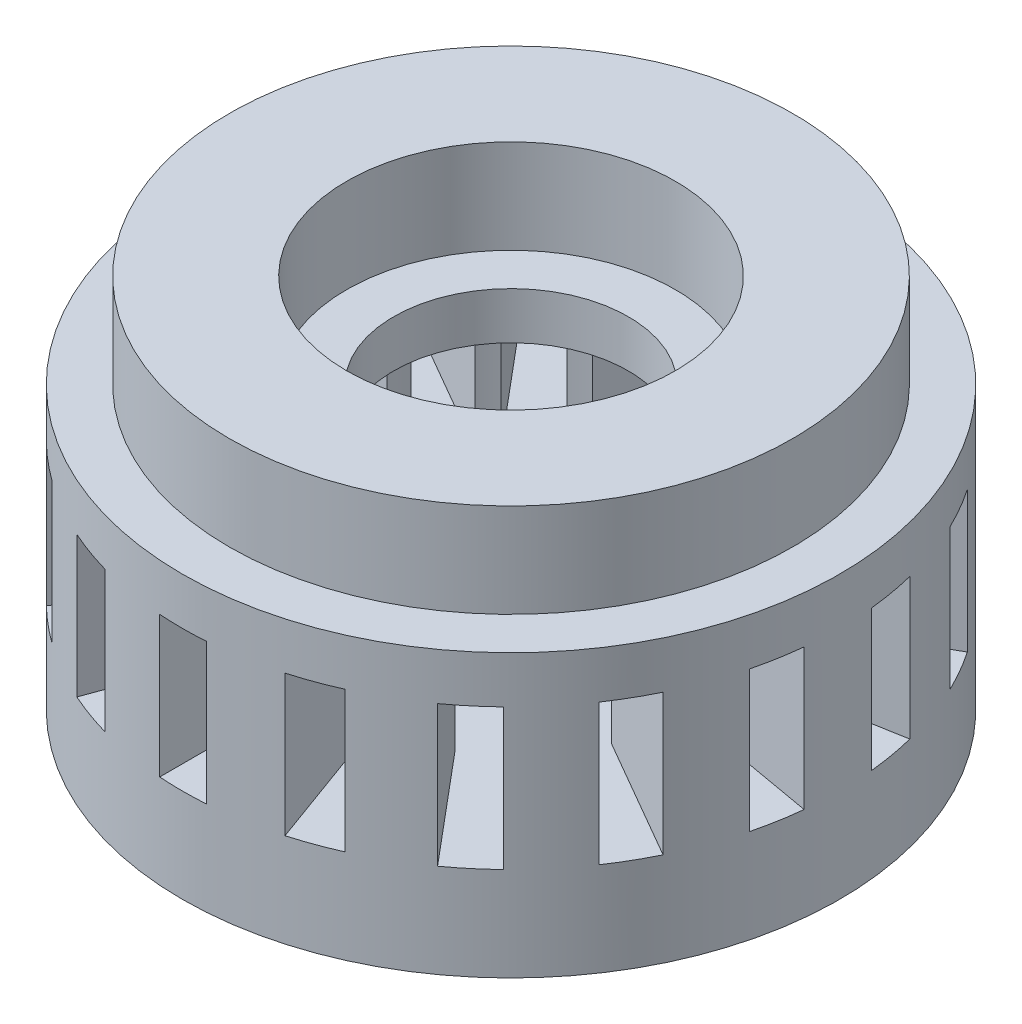
SolidWorks part; units mm, degrees
ref_plane "前视基准面" through (0, 0, 0) normal (0, 0, 1) x (1, 0, 0)
ref_plane "上视基准面" through (0, 0, 0) normal (0, 1, 0) x (1, 0, 0)
ref_plane "右视基准面" through (0, 0, 0) normal (1, 0, 0) x (0, 0, -1)
sketch "草图1" plane through (0, 0, 0) normal (0, 1, 0) x (1, 0, 0)
  line L0 (-1.299, 0.75) -> (1.299, 0.75)
  line L1 (-1.299, 0.75) -> (0, 0) construction
  line L2 (0, 0) -> (1.299, 0.75) construction
  arc A0 (-1.299, 0.75) -> (1.299, 0.75) centre (0, 0) ccw
  circle A1 centre (0, 0) radius 3
  dimension "D1" = 1.5
  dimension "D2" = 6
  dimension "D3" = 120
extrude "凸台-拉伸1" add sketch "草图1" along normal blind 1.5
sketch "草图2" plane through (0, 1.5, 0) normal (0, 1, 0) x (1, 0, 0)
  line L1 (1.299, 0.75) -> (-1.299, 0.75)
  line L2 (1.299, 0.75) -> (-1.299, 0.75)
  circle A0 centre (0, 0) radius 7
  arc A1 (-1.299, 0.75) -> (1.299, 0.75) centre (0, 0) ccw
  arc A2 (-1.299, 0.75) -> (1.299, 0.75) centre (0, 0) ccw
  dimension "D2" = 14
  dimension "D1" = 0
extrude "凸台-拉伸2" add sketch "草图2" along normal blind 2
sketch "草图3" plane through (0, 3.5, 0) normal (0, 1, 0) x (1, 0, 0)
  circle A0 centre (0, 0) radius 6.5 construction
  circle A1 centre (0, 0) radius 7
  circle A2 centre (0, 0) radius 7
  dimension "D2" = 13
  dimension "D1" = 0
extrude "凸台-拉伸3" add sketch "草图3" along normal blind 3
sketch "草图4" plane through (0, 0, 0) normal (0, 0, 1) x (1, 0, 0)
  line L0 (0, 6.5) -> (0, 0) construction
  line L2 (7, 6.5) -> (-7, 6.5) construction
  line L3 (-0.5, 3.5) -> (0.5, 3.5)
  line L4 (-0.5, 3.5) -> (-0.5, 6.5)
  line L5 (-0.5, 6.5) -> (0.5, 6.5)
  line L6 (0.5, 3.5) -> (0.5, 6.5)
  line L7 (-0.5, 3.5) -> (0.5, 6.5) construction
  line L8 (-0.5, 6.5) -> (0.5, 3.5) construction
  line L9 (-3, 1.5) -> (3, 1.5) construction
  point P5 (0, 5)
  dimension "D1" = 2
  dimension "D2" = 1
extrude "切除-拉伸1" cut sketch "草图4" against normal through all and the other way through all
pattern_circular "阵列(圆周)1" count 9 over 360 about axis through (0, 0, 0) along (0, 1, 0) of "切除-拉伸1"
sketch "草图8" plane through (0, 6.5, 0) normal (0, 1, 0) x (1, 0, 0)
  circle A0 centre (0, 0) radius 4
  dimension "D1" = 8
extrude "切除-拉伸3" cut sketch "草图8" against normal blind 3
sketch "草图5" plane through (0, 6.5, 0) normal (0, 1, 0) x (1, 0, 0)
  circle A0 centre (0, 0) radius 7
  arc A1 (4.105, -5.67) -> (4.871, -5.0272) centre (0, 0) ccw construction
extrude "凸台-拉伸4" add sketch "草图5" along normal blind 1
sketch "草图6" plane through (0, 7.5, 0) normal (0, 1, 0) x (1, 0, 0)
  circle A0 centre (0, 0) radius 6
  dimension "D1" = 12
extrude "凸台-拉伸5" add sketch "草图6" along normal blind 2
sketch "草图7" plane through (0, 9.5, 0) normal (0, 1, 0) x (1, 0, 0)
  circle A0 centre (0, 0) radius 3.5
  dimension "D1" = 7
extrude "切除-拉伸2" cut sketch "草图7" against normal blind 2
sketch "草图9" plane through (0, 7.5, 0) normal (0, 1, 0) x (1, 0, 0)
  circle A0 centre (0, 0) radius 2.5
  dimension "D1" = 5
extrude "切除-拉伸4" cut sketch "草图9" against normal blind 1
